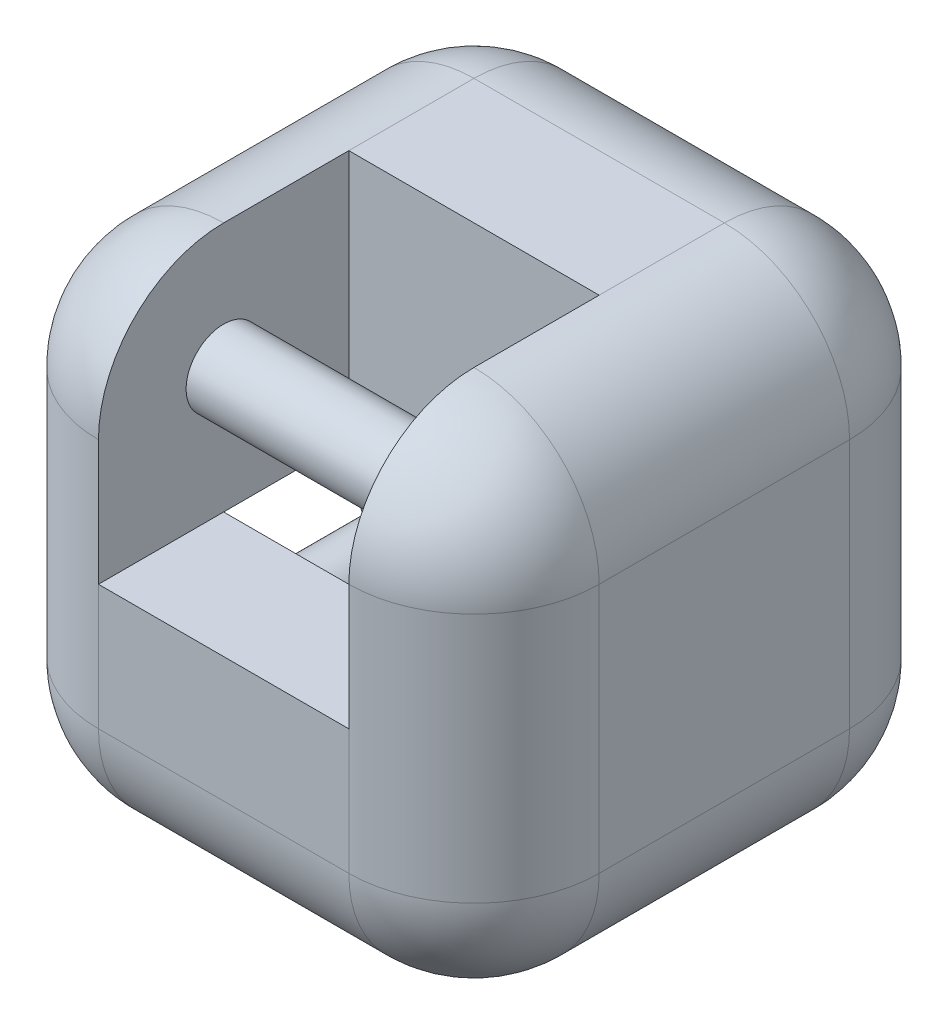
SolidWorks part; units mm, degrees
ref_plane "前视基准面" through (0, 0, 0) normal (0, 0, 1) x (1, 0, 0)
ref_plane "上视基准面" through (0, 0, 0) normal (0, 1, 0) x (1, 0, 0)
ref_plane "右视基准面" through (0, 0, 0) normal (1, 0, 0) x (0, 0, -1)
sketch "草图1" plane through (0, 0, 0) normal (0, 0, 1) x (1, 0, 0)
  line L1 (-23.4081, 37.1656) -> (-3.4081, 37.1656)
  line L2 (-23.4081, 37.1656) -> (-23.4081, 17.1656)
  line L3 (-23.4081, 17.1656) -> (-3.4081, 17.1656)
  line L4 (-3.4081, 37.1656) -> (-3.4081, 17.1656)
  dimension "D1" = 20
extrude "凸台-拉伸1" add sketch "草图1" along normal blind 20
fillet "圆角1" radius 5 12 edges at (-23.4081, 27.1656, 0) (-23.4081, 17.1656, 10) (-13.4081, 17.1656, 0) (-3.4081, 27.1656, 0) (-13.4081, 37.1656, 0) (-23.4081, 37.1656, 10) (-23.4081, 27.1656, 20) (-13.4081, 37.1656, 20) (-3.4081, 37.1656, 10) (-3.4081, 17.1656, 10) (-3.4081, 27.1656, 20) (-13.4081, 17.1656, 20)
ref_plane "基准面1" through (-8.4081, 0, 0) normal (-1, 0, 0) x (0, 0, 1)
sketch "草图2" plane through (-8.4081, 0, 0) normal (-1, 0, 0) x (0, 0, 1)
  line L1 (10, 27.1656) -> (20, 27.1656)
  line L2 (10, 27.1656) -> (10, 37.1656)
  line L3 (10, 37.1656) -> (20, 37.1656)
  line L4 (20, 27.1656) -> (20, 37.1656)
  line L5 (10, 27.1656) -> (20, 37.1656) construction
  line L6 (10, 37.1656) -> (20, 27.1656) construction
  point P0 (15, 32.1656)
extrude "切除-拉伸1" cut sketch "草图2" along normal blind 10
ref_plane "基准面2" through (0, 0, 15) normal (0, 0, -1) x (-1, 0, 0)
sketch "草图3" plane through (0, 0, 15) normal (0, 0, -1) x (-1, 0, 0)
  line L1 (13.4081, 27.1656) -> (23.4081, 27.1656)
  line L2 (13.4081, 27.1656) -> (13.4081, 17.1656)
  line L3 (13.4081, 17.1656) -> (23.4081, 17.1656)
  line L4 (23.4081, 27.1656) -> (23.4081, 17.1656)
  line L5 (13.4081, 27.1656) -> (23.4081, 17.1656) construction
  line L6 (13.4081, 17.1656) -> (23.4081, 27.1656) construction
  point P0 (18.4081, 22.1656)
extrude "切除-拉伸2" cut sketch "草图3" along normal blind 10
sketch "草图4" plane through (-8.4081, 0, 0) normal (-1, 0, 0) x (0, 0, 1)
  circle A0 centre (15, 32.1656) radius 1.5
  dimension "D1" = 3
extrude "凸台-拉伸2" add sketch "草图4" along normal blind 10 separate body
sketch "草图5" plane through (0, 0, 15) normal (0, 0, -1) x (-1, 0, 0)
  circle A0 centre (18.4081, 22.1656) radius 1.5
  dimension "D1" = 3
extrude "凸台-拉伸3" add sketch "草图5" along normal blind 10 separate body
